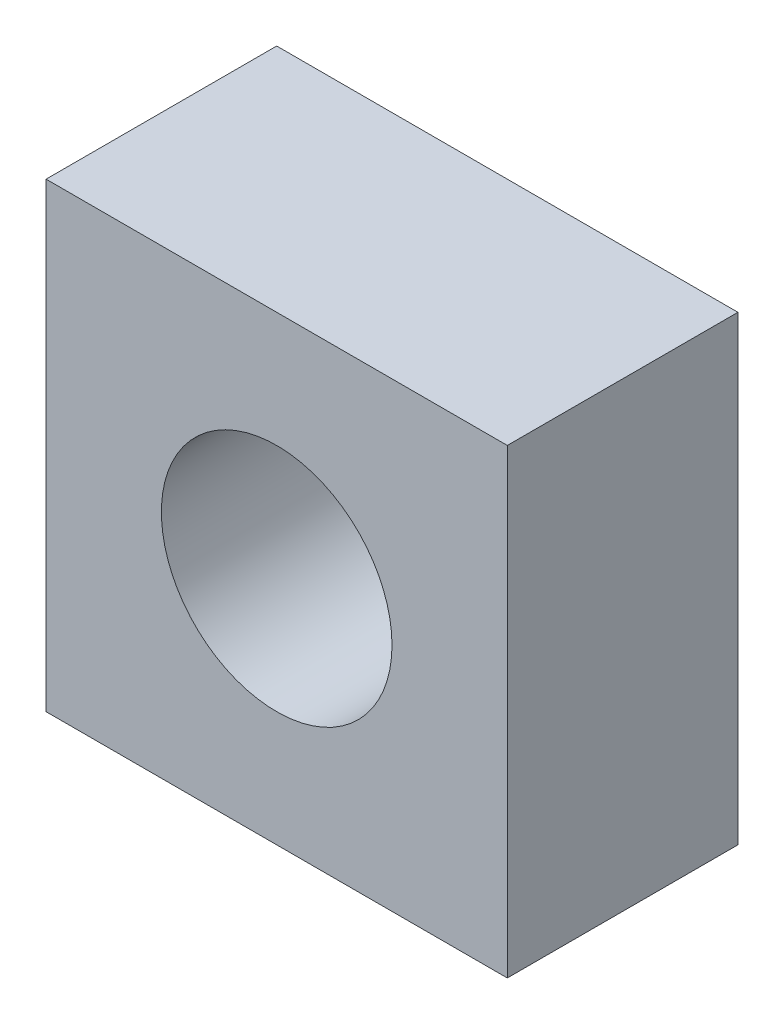
SolidWorks part; units mm, degrees
ref_plane "Front Plane" through (0, 0, 0) normal (0, 0, 1) x (1, 0, 0)
ref_plane "Top Plane" through (0, 0, 0) normal (0, 1, 0) x (1, 0, 0)
ref_plane "Right Plane" through (0, 0, 0) normal (1, 0, 0) x (0, 0, -1)
sketch "Sketch1" plane through (0, 0, 0) normal (0, 0, 1) x (1, 0, 0)
  line L1 (0, 0) -> (40, 0)
  line L2 (0, 0) -> (0, 40)
  line L3 (0, 40) -> (40, 40)
  line L4 (40, 0) -> (40, 40)
  circle A0 centre (20, 20) radius 10
extrude "Boss-Extrude1" add sketch "Sketch1" along normal blind 20
